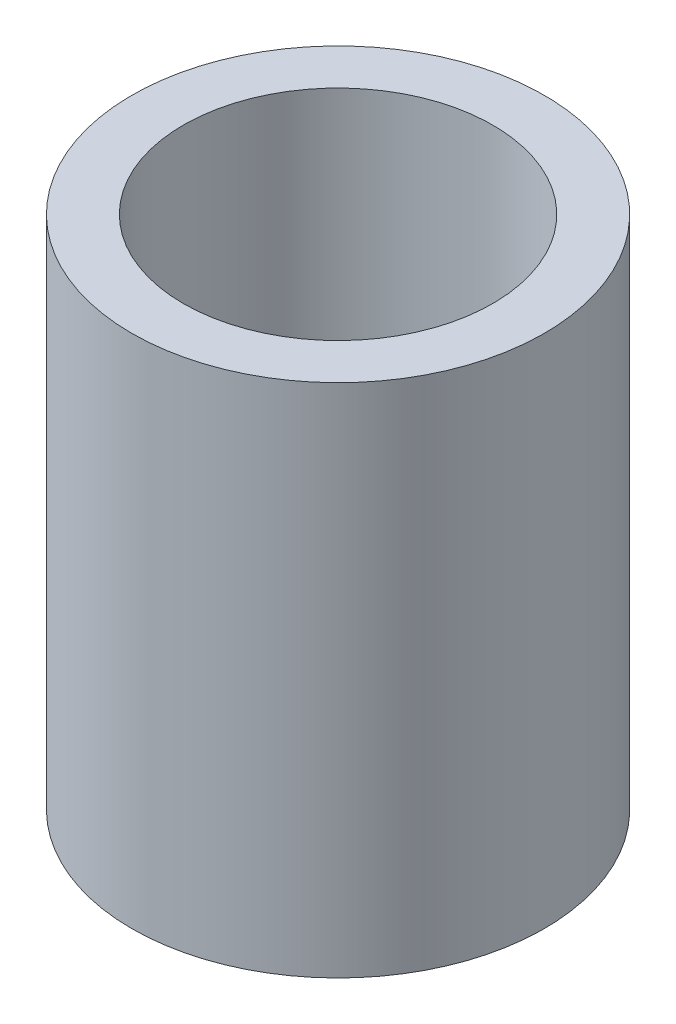
SolidWorks part; units mm, degrees
ref_plane "Front Plane" through (0, 0, 0) normal (0, 0, 1) x (1, 0, 0)
ref_plane "Top Plane" through (0, 0, 0) normal (0, 1, 0) x (1, 0, 0)
ref_plane "Right Plane" through (0, 0, 0) normal (1, 0, 0) x (0, 0, -1)
sketch "Sketch1" plane through (0, 0, 0) normal (0, 1, 0) x (1, 0, 0)
  circle A0 centre (0, 0) radius 20.32
  circle A1 centre (0, 0) radius 15.24
extrude "Boss-Extrude1" add sketch "Sketch1" along normal blind 50.8
